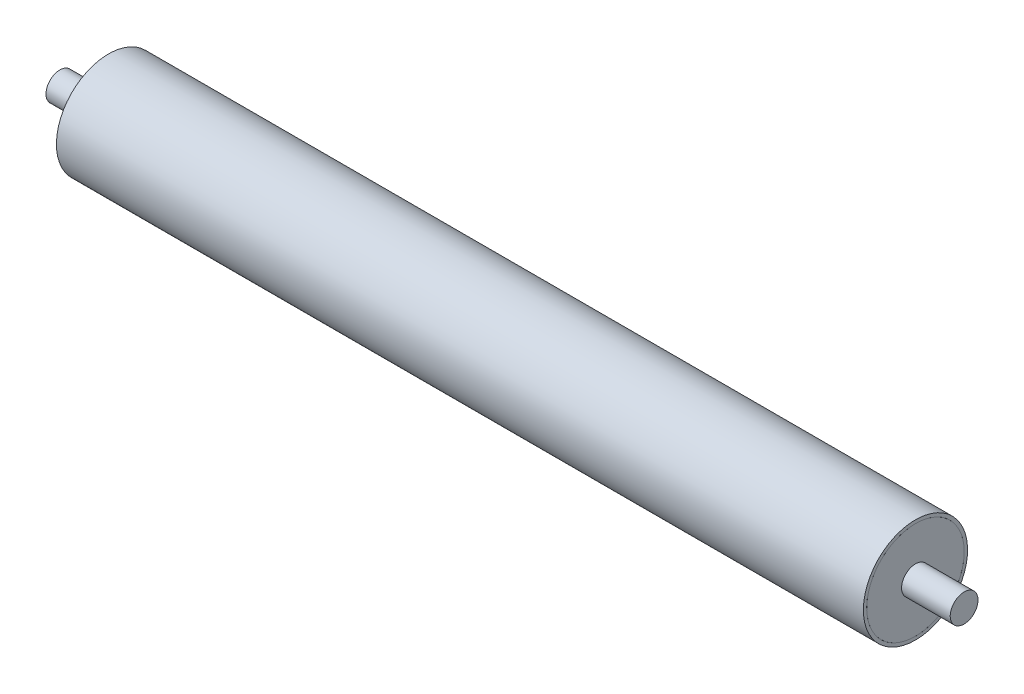
SolidWorks part; units mm, degrees
material "AISI 304"
ref_plane "Front Plane" through (0, 0, 0) normal (0, 0, 1) x (1, 0, 0)
ref_plane "Top Plane" through (0, 0, 0) normal (0, 1, 0) x (1, 0, 0)
ref_plane "Right Plane" through (0, 0, 0) normal (1, 0, 0) x (0, 0, -1)
sketch "Sketch1" plane through (0, 0, 0) normal (0, 0, 1) x (1, 0, 0)
  line L0 (-290.3, 37.5) -> (290.3, 37.5)
  line L1 (290.3, 37.5) -> (290.3, 35.1005)
  line L2 (290.3, 35.1005) -> (-290.3, 35.1005)
  line L3 (-290.3, 35.1005) -> (-290.3, 37.5)
  line L4 (-290.3, 0) -> (290.3, 0) construction
  point P8 (0, 0)
  dimension "D1" = 580.6
  dimension "D2" = 75
  dimension "D3" = 70.201
revolve "Revolve1" add sketch "Sketch1" angle 360 about L4
sketch "Sketch2" plane through (-290.3, 0, 0) normal (-1, 0, 0) x (0, 0, 1)
  circle A1 centre (0, 0) radius 35.1
  circle A2 centre (0, 0) radius 10.0005
  dimension "D1" = 20.001
  dimension "D2" = 70.2
extrude "Boss-Extrude1" add sketch "Sketch2" against normal blind 10
sketch "Sketch3" plane through (290.3, 0, 0) normal (1, 0, 0) x (0, 0, -1)
  circle A0 centre (0, 0) radius 10.0005 construction
  circle A1 centre (0, 0) radius 35.1
  circle A2 centre (0, 0) radius 35.1
  circle A3 centre (0, 0) radius 10.0005
  dimension "D1" = 0
extrude "Boss-Extrude2" add sketch "Sketch3" against normal blind 10 separate body
sketch "Sketch4" plane through (0, 0, 0) normal (0, 0, 1) x (1, 0, 0)
  line L0 (-325.3, 10) -> (325.3, 10)
  line L1 (-290.3, 10.0005) -> (-290.3, -10.0005) construction
  line L6 (325.3, 0) -> (-325.3, 0) construction
  line L8 (-290.3, 10.0005) -> (-290.3, -10.0005) construction
  line L9 (-325.3, 10) -> (-325.3, 0)
  line L10 (-325.3, 0) -> (325.3, 0) construction
  line L11 (-325.3, 0) -> (325.3, 0)
  line L14 (325.3, 10) -> (325.3, 0)
  line L17 (-290.3, 35.1) -> (-290.3, -35.1) construction
  line L18 (290.3, -35.1) -> (290.3, 35.1) construction
  point P17 (325.3, 5)
  dimension "D2" = 35
  dimension "D5" = 35
  dimension "D7" = 20
revolve "Revolve3" add sketch "Sketch4" angle 360 about L11
